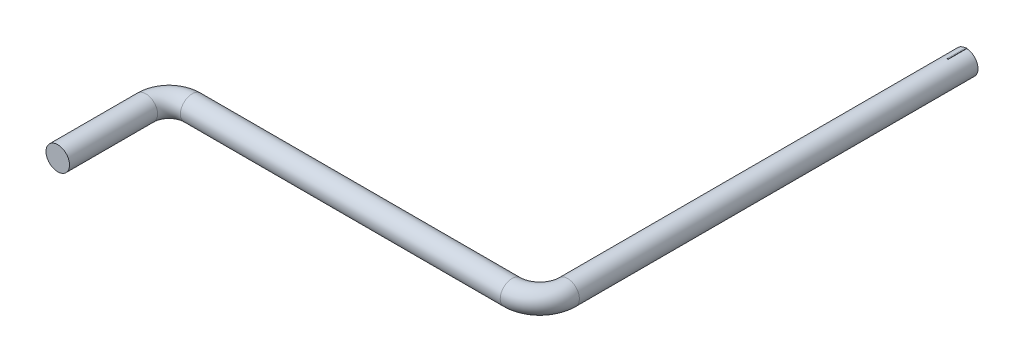
SolidWorks part; units mm, degrees
ref_plane "Alzado" through (0, 0, 0) normal (0, 0, 1) x (1, 0, 0)
ref_plane "Planta" through (0, 0, 0) normal (0, 1, 0) x (1, 0, 0)
ref_plane "Vista lateral" through (0, 0, 0) normal (1, 0, 0) x (0, 0, -1)
sketch "Croquis1" plane through (0, 0, 0) normal (0, 0, 1) x (1, 0, 0)
  circle A0 centre (0, 0) radius 12.7
  dimension "D1" = 25.4
extrude "Saliente-Extruir1" add sketch "Croquis1" along normal blind 10
sketch3d "Croquis3D1"
  line L0 (0, 0, 10) -> (0, 0, 430)
  line L1 (0, 0, 10) -> (0, 0, 0) construction
  line L2 (-30, 0, 460) -> (-375, 0, 460)
  line L3 (-400, 0, 485) -> (-400, 0, 580)
  arc A0 (0, 0, 430) -> (-30, 0, 460) centre (-30, 0, 430) ccw
  arc A1 (-375, 0, 460) -> (-400, 0, 485) centre (-375, 0, 485) ccw
  point P7 (0, 0, 460)
  point P8 (-30, -30, 430)
  point P12 (-400, 0, 460)
  point P13 (-375, 25, 485)
  dimension "D3" = 30
  dimension "D5" = 25
  dimension "D1" = 450
  dimension "D2" = 400
  dimension "D4" = 120
sketch "Croquis2" plane through (0, 0, 10) normal (0, 0, 1) x (1, 0, 0)
  circle A0 centre (0, 0) radius 12.7
  dimension "D1" = 25.4
sweep "Barrer1" add profiles "Croquis2" path "Croquis3D1"
sketch "Croquis3" plane through (0, 0, 0) normal (0, 0, -1) x (-1, 0, 0)
  line L1 (-0.5558, 12.3691) -> (0.5558, 12.3691)
  line L2 (-0.5558, 12.3691) -> (-0.5558, 13.0309)
  line L3 (-0.5558, 13.0309) -> (0.5558, 13.0309)
  line L4 (0.5558, 12.3691) -> (0.5558, 13.0309)
  line L5 (-0.5558, 12.3691) -> (0.5558, 13.0309) construction
  line L6 (-0.5558, 13.0309) -> (0.5558, 12.3691) construction
  circle A0 centre (0, 0) radius 12.7 construction
  point P0 (0, 12.7)
extrude "Saliente-Extruir2" add sketch "Croquis3" against normal blind 20
